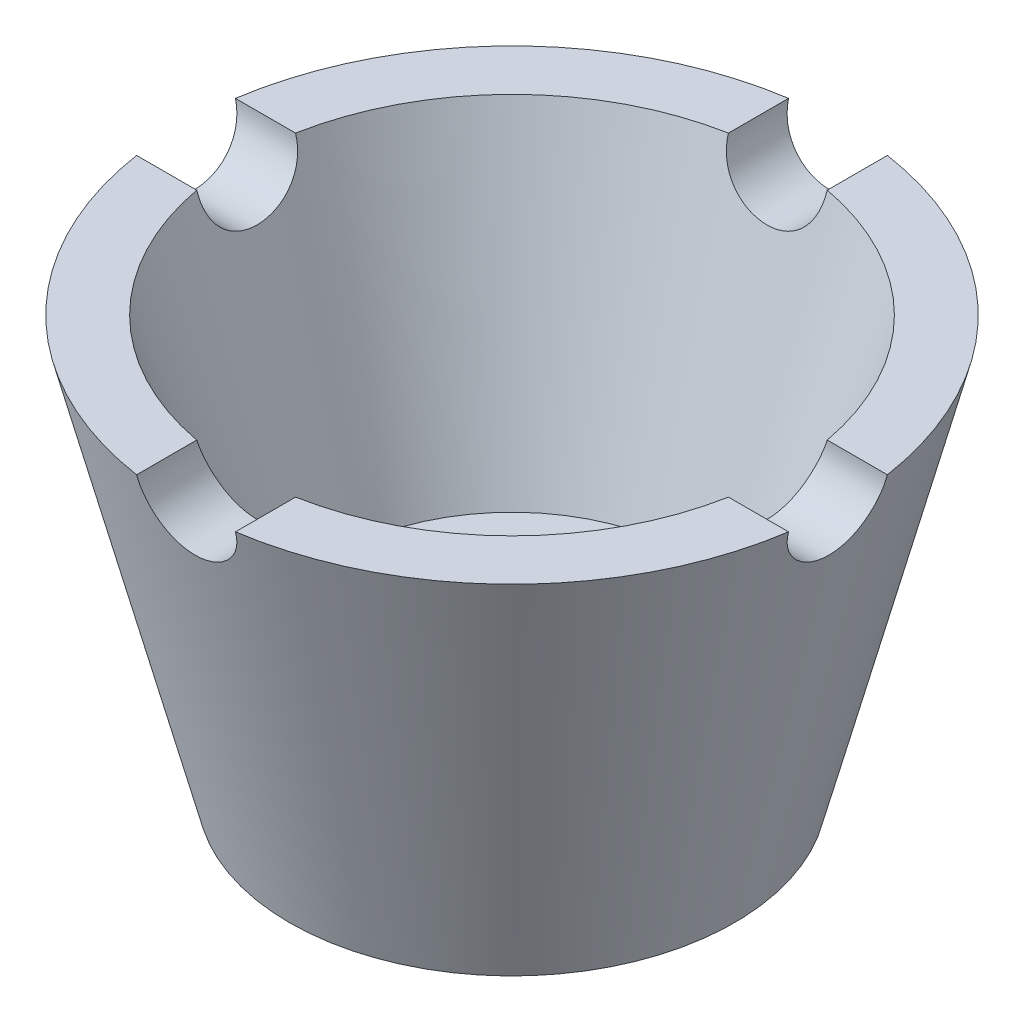
SolidWorks part; units mm, degrees
ref_plane "Front Plane" through (0, 0, 0) normal (0, 0, 1) x (1, 0, 0)
ref_plane "Top Plane" through (0, 0, 0) normal (0, 1, 0) x (1, 0, 0)
ref_plane "Right Plane" through (0, 0, 0) normal (1, 0, 0) x (0, 0, -1)
sketch "Sketch1" plane through (0, 0, 0) normal (0, 0, 1) x (1, 0, 0)
  line L0 (0, 40.4587) -> (0, -63) construction
  line L7 (-31.0183, 0) -> (76.0183, 0) construction
  line L8 (11.25, 0) -> (11.25, 12)
  line L9 (11.25, 12) -> (18, 12)
  line L10 (18, 12) -> (27.3578, 42)
  line L11 (27.3578, 42) -> (33.3578, 42)
  line L12 (33.3578, 42) -> (22.5, 0)
  line L13 (22.5, 0) -> (11.25, 0)
  point P7 (11.25, 6)
  point P12 (14.625, 12)
  dimension "D1" = 42
  dimension "D2" = 11.25
  dimension "D3" = 22.5
  dimension "D4" = 18
  dimension "D5" = 6
  dimension "D6" = 12
revolve "Revolve1" add sketch "Sketch1" angle 360 about L0
sketch "Sketch2" plane through (0, 0, 0) normal (0, 0, 1) x (1, 0, 0)
  line L0 (27.3578, 42) -> (-27.3578, 42) construction
  circle A0 centre (0, 42) radius 5
  dimension "D1" = 10
extrude "Cut-Extrude1" cut sketch "Sketch2" against normal through all both and the other way through all
sketch "Sketch3" plane through (0, 0, 0) normal (1, 0, 0) x (0, 0, -1)
  line L0 (32.9809, 42) -> (-32.9809, 42) construction
  circle A0 centre (0, 42) radius 5
  dimension "D1" = 10
extrude "Cut-Extrude2" cut sketch "Sketch3" against normal through all both and the other way through all
